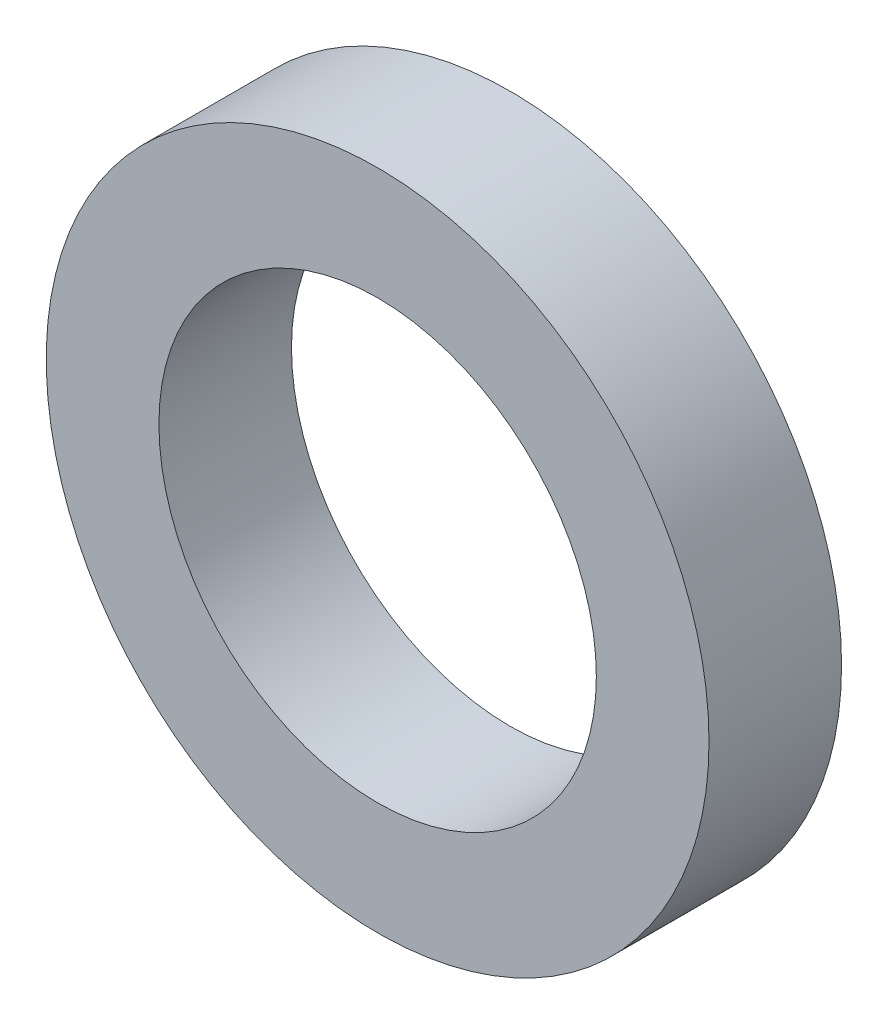
SolidWorks part; units mm, degrees
ref_plane "Front" through (0, 0, 0) normal (0, 0, 1) x (1, 0, 0)
ref_plane "Top" through (0, 0, 0) normal (0, 1, 0) x (1, 0, 0)
ref_plane "Right" through (0, 0, 0) normal (1, 0, 0) x (0, 0, -1)
sketch "Sketch1" plane through (0, 0, 0) normal (0, 0, 1) x (1, 0, 0)
  circle A0 centre (0, 0) radius 4.191
  circle A2 centre (0, 0) radius 6.35
  dimension "D1" = 8.382
  dimension "D2" = 12.7
extrude "Boss-Extrude1" add sketch "Sketch1" along normal blind 2.54
chamfer "Chamfer1" [suppressed] distance 1.27 angle 45
